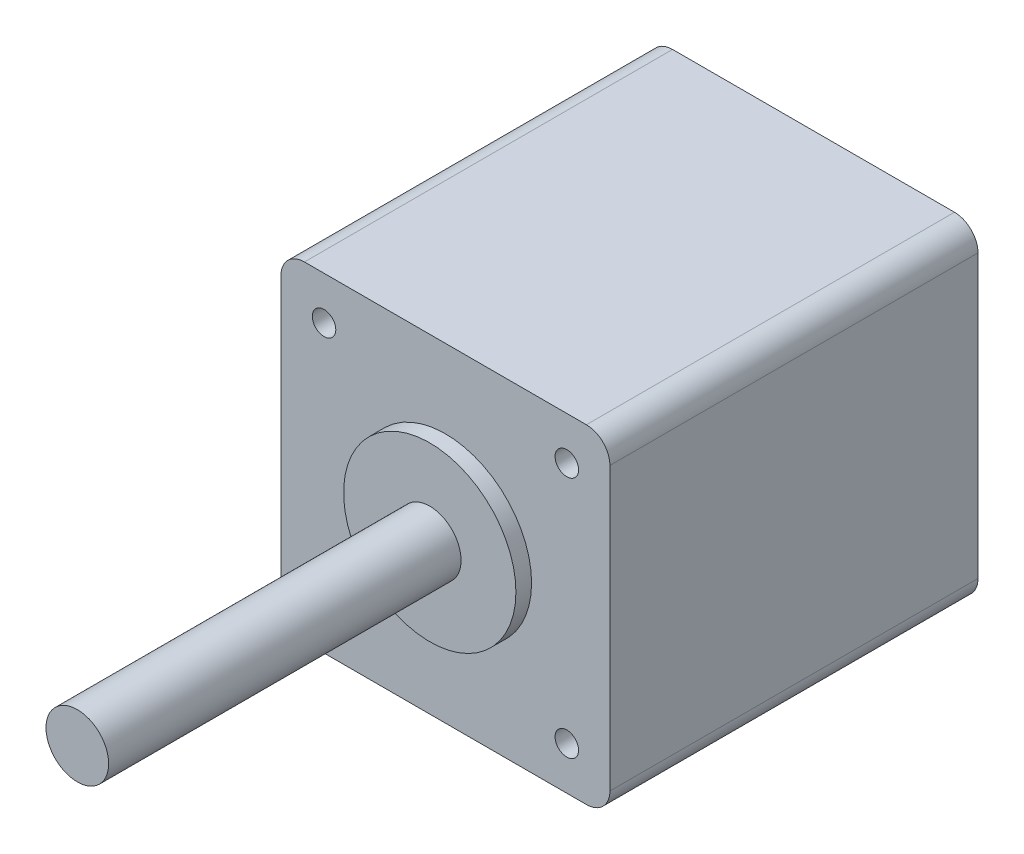
SolidWorks part; units mm, degrees
ref_plane "前视基准面" through (0, 0, 0) normal (0, 0, 1) x (1, 0, 0)
ref_plane "上视基准面" through (0, 0, 0) normal (0, 1, 0) x (1, 0, 0)
ref_plane "右视基准面" through (0, 0, 0) normal (1, 0, 0) x (0, 0, -1)
sketch "草图1" plane through (0, 0, 0) normal (0, 0, 1) x (1, 0, 0)
  line L0 (0, 0) -> (0, -21) construction
  line L1 (18, -21) -> (-18, -21)
  line L2 (21, -18) -> (21, 18)
  line L3 (18, 21) -> (-18, 21)
  line L4 (-21, -18) -> (-21, 18)
  line L5 (21, -21) -> (-21, 21) construction
  line L6 (21, 21) -> (-21, -21) construction
  line L7 (0, 0) -> (21, 0) construction
  arc A0 (-21, -18) -> (-18, -21) centre (-18, -18) ccw
  arc A1 (18, -21) -> (21, -18) centre (18, -18) ccw
  arc A2 (21, 18) -> (18, 21) centre (18, 18) ccw
  arc A3 (-18, 21) -> (-21, 18) centre (-18, 18) ccw
  point P0 (0, 0)
  point P18 (11.5, -11.5)
  point P21 (-11.5, -11.5)
  point P24 (-11.5, 11.5)
  point P25 (11.5, 11.5)
  point P28 (0, 0)
  dimension "D2" = 3
  dimension "D3" = 23
  dimension "D1" = 42
  dimension "28" = 42
extrude "凸台-拉伸1" add sketch "草图1" along normal blind 47
sketch "草图2" plane through (0, 0, 47) normal (0, 0, 1) x (1, 0, 0)
  circle A0 centre (0, 0) radius 11
  dimension "D1" = 22
extrude "凸台-拉伸2" add sketch "草图2" along normal blind 2
sketch "草图3" plane through (0, 0, 49) normal (0, 0, 1) x (1, 0, 0)
  circle A0 centre (0, 0) radius 4
  dimension "D1" = 8
extrude "凸台-拉伸3" add sketch "草图3" along normal blind 45
cosmetic thread "装饰螺纹线1" parameters "D2"=4.917
sketch "草图6" plane through (0, 0, 47) normal (0, 0, 1) x (1, 0, 0)
  line L1 (0, 29.3895) -> (0, -23.5) construction
  line L2 (-35.2004, 0) -> (32.3671, 0) construction
  circle A0 centre (-15.5, 15.5) radius 1.5
  circle A1 centre (15.5, 15.5) radius 1.5
  circle A2 centre (15.5, -15.5) radius 1.5
  circle A3 centre (-15.5, -15.5) radius 1.5
  point P15 (0, 0)
  dimension "D1" = 3
  dimension "D2" = 15.5
  dimension "D3" = 15.5
  dimension "D4" = 4
extrude "切除-拉伸2" cut sketch "草图6" against normal blind 3.5
